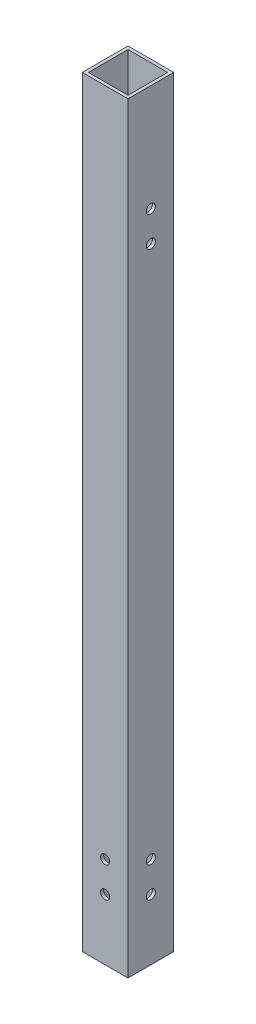
SolidWorks part; units mm, degrees
ref_plane "Front Plane" through (0, 0, 0) normal (0, 0, 1) x (1, 0, 0)
ref_plane "Top Plane" through (0, 0, 0) normal (0, 1, 0) x (1, 0, 0)
ref_plane "Right Plane" through (0, 0, 0) normal (1, 0, 0) x (0, 0, -1)
sketch "Sketch1" plane through (0, 0, 0) normal (0, 1, 0) x (1, 0, 0)
  line L1 (-15, 0) -> (-15, 15)
  line L2 (-15, 15) -> (15, 15)
  line L3 (15, 15) -> (15, -15)
  line L4 (15, -15) -> (-15, -15)
  line L5 (-15, -15) -> (-15, 0)
extrude "Boss-Extrude1" add sketch "Sketch1" along normal blind 500
sketch "Sketch3" plane through (0, 500, 0) normal (0, 1, 0) x (1, 0, 0)
  line L3 (-13, 13) -> (-13, -13)
  line L4 (-13, -13) -> (13, -13)
  line L5 (13, -13) -> (13, 13)
  line L6 (13, 13) -> (-13, 13)
extrude "Cut-Extrude1" cut sketch "Sketch3" against normal blind 500
sketch "Sketch5" plane through (15, 0, 0) normal (1, 0, 0) x (0, 0, -1)
  circle A0 centre (0, 60) radius 3
  circle A1 centre (0, 40) radius 3
extrude "Cut-Extrude2" cut sketch "Sketch5" against normal blind 30
sketch "Sketch6" plane through (0, 0, 15) normal (0, 0, 1) x (1, 0, 0)
  circle A0 centre (0, 40) radius 3
  circle A1 centre (0, 60) radius 3
extrude "Cut-Extrude3" cut sketch "Sketch6" against normal blind 30
sketch "Sketch9" plane through (-15, 0, 0) normal (-1, 0, 0) x (0, 0, 1)
  circle A0 centre (0, 430) radius 3
  circle A1 centre (0, 410) radius 3
extrude "Cut-Extrude6" cut sketch "Sketch9" against normal blind 30
